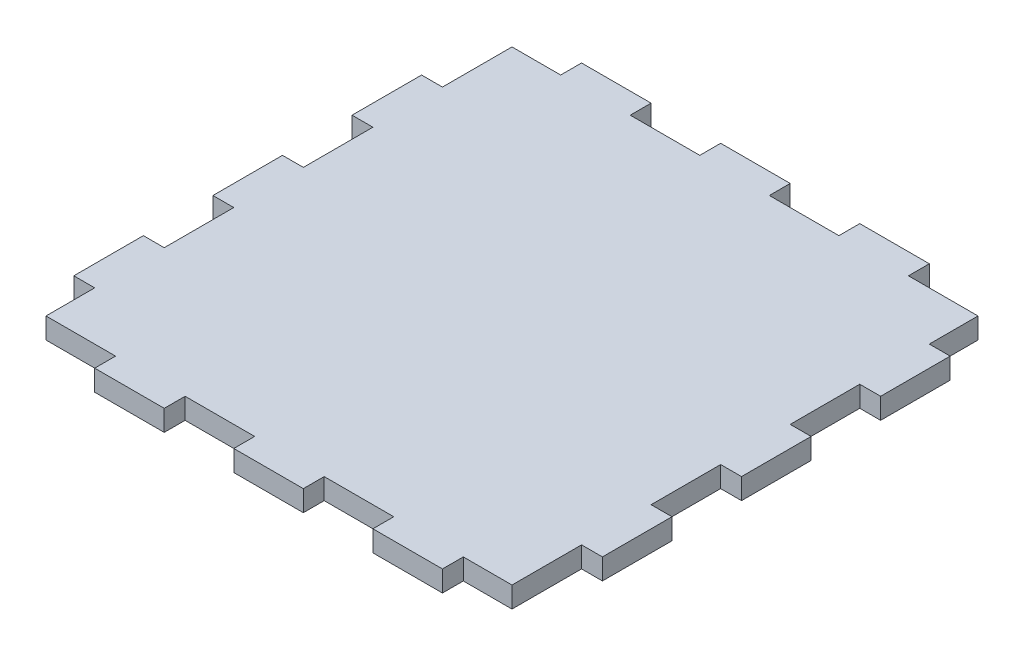
SolidWorks part; units mm, degrees
ref_plane "Front Plane" through (0, 0, 0) normal (0, 0, 1) x (1, 0, 0)
ref_plane "Top Plane" through (0, 0, 0) normal (0, 1, 0) x (1, 0, 0)
ref_plane "Right Plane" through (0, 0, 0) normal (1, 0, 0) x (0, 0, -1)
sketch "Sketch1" plane through (0, 0, 0) normal (0, 1, 0) x (1, 0, 0)
  line L0 (33.5, 16.5) -> (36.5, 16.5)
  line L1 (-33.5, -33.5) -> (33.5, -33.5)
  line L2 (-33.5, -33.5) -> (-33.5, 33.5)
  line L3 (-33.5, 33.5) -> (33.5, 33.5)
  line L4 (33.5, -33.5) -> (33.5, 33.5)
  line L5 (-33.5, -33.5) -> (33.5, 33.5) construction
  line L6 (-33.5, 33.5) -> (33.5, -33.5) construction
  line L7 (-6.5, 33.5) -> (3.5, 33.5)
  line L8 (-6.5, 33.5) -> (-6.5, 36.5)
  line L9 (-6.5, 36.5) -> (3.5, 36.5)
  line L10 (3.5, 33.5) -> (3.5, 36.5)
  line L11 (-6.5, 33.5) -> (3.5, 36.5) construction
  line L12 (-6.5, 36.5) -> (3.5, 33.5) construction
  line L13 (-26.5, 33.5) -> (-16.5, 33.5)
  line L14 (-26.5, 33.5) -> (-26.5, 36.5)
  line L15 (-26.5, 36.5) -> (-16.5, 36.5)
  line L16 (-16.5, 33.5) -> (-16.5, 36.5)
  line L17 (-26.5, 33.5) -> (-16.5, 36.5) construction
  line L18 (-26.5, 36.5) -> (-16.5, 33.5) construction
  line L19 (13.5, 33.5) -> (23.5, 33.5)
  line L20 (13.5, 33.5) -> (13.5, 36.5)
  line L21 (13.5, 36.5) -> (23.5, 36.5)
  line L22 (23.5, 33.5) -> (23.5, 36.5)
  line L23 (13.5, 33.5) -> (23.5, 36.5) construction
  line L24 (13.5, 36.5) -> (23.5, 33.5) construction
  line L25 (36.5, 26.5) -> (36.5, 16.5)
  line L26 (33.5, 26.5) -> (36.5, 26.5)
  line L27 (33.5, 6.5) -> (36.5, 6.5)
  line L28 (36.5, 6.5) -> (36.5, -3.5)
  line L29 (33.5, -3.5) -> (36.5, -3.5)
  line L30 (33.5, -13.5) -> (36.5, -13.5)
  line L31 (36.5, -13.5) -> (36.5, -23.5)
  line L32 (33.5, -23.5) -> (36.5, -23.5)
  line L33 (16.5, -33.5) -> (16.5, -36.5)
  line L34 (26.5, -36.5) -> (16.5, -36.5)
  line L35 (26.5, -33.5) -> (26.5, -36.5)
  line L36 (6.5, -33.5) -> (6.5, -36.5)
  line L37 (6.5, -36.5) -> (-3.5, -36.5)
  line L38 (-3.5, -33.5) -> (-3.5, -36.5)
  line L39 (-13.5, -33.5) -> (-13.5, -36.5)
  line L40 (-13.5, -36.5) -> (-23.5, -36.5)
  line L41 (-23.5, -33.5) -> (-23.5, -36.5)
  line L42 (-33.5, -16.5) -> (-36.5, -16.5)
  line L43 (-36.5, -26.5) -> (-36.5, -16.5)
  line L44 (-33.5, -26.5) -> (-36.5, -26.5)
  line L45 (-33.5, -6.5) -> (-36.5, -6.5)
  line L46 (-36.5, -6.5) -> (-36.5, 3.5)
  line L47 (-33.5, 3.5) -> (-36.5, 3.5)
  line L48 (-33.5, 13.5) -> (-36.5, 13.5)
  line L49 (-36.5, 13.5) -> (-36.5, 23.5)
  line L50 (-33.5, 23.5) -> (-36.5, 23.5)
  point P0 (0, 0)
  point P10 (-1.5, 35)
  point P15 (-21.5, 35)
  point P20 (18.5, 35)
  point P21 (-6.5, 35)
  point P61 (0, 0)
  dimension "D1" = 67
  dimension "D2" = 67
  dimension "D3" = 3
  dimension "D4" = 3
  dimension "D5" = 3
  dimension "D6" = 10
  dimension "D7" = 10
  dimension "D8" = 10
  dimension "D9" = 10
  dimension "D10" = 10
  dimension "D12" = 7
  dimension "D11" = 4
extrude "Boss-Extrude1" add sketch "Sketch1" along normal blind 3 contours L1 L4 L3 L2 | L44 L2 L42 L43 | L2 L47 L46 L45 | L2 L50 L49 L48 | L1 L41 L40 L39 | L1 L38 L37 L36 | L35 L1 L33 L34 | L4 L32 L31 L30 | L4 L29 L28 L27 | L26 L4 L0 L25 | L3 L22 L21 L20 | L3 L10 L9 L8 | L3 L16 L15 L14
sketch "Sketch2" plane through (0, 3, 0) normal (0, 1, 0) x (1, 0, 0)
  line L0 (-33.5, 28.5) -> (33.5, 28.5)
  line L1 (-33.5, 23.5) -> (-33.5, 33.5) construction
  line L2 (33.5, 26.5) -> (33.5, 33.5) construction
sketch "Sketch3" plane through (0, 0, 0) normal (0, -1, 0) x (1, 0, 0)
  line L0 (-135.7232, -654.8177) -> (-802.3899, -654.8177) construction
  line L1 (19.4689, -11.5963) -> (-19.7557, -11.5963) construction
  line L2 (-22.7557, -8.5963) -> (-22.7557, 12.0128) construction
  line L3 (-19.7557, 15.0128) -> (19.4689, 15.0128) construction
  line L4 (22.4689, 12.0128) -> (22.4689, -8.5963) construction
  line L5 (10.2909, -11.5963) -> (10.2909, -13.5661) construction
  line L6 (-13.4873, -5.6818) -> (-20.4372, -5.6818) construction
  line L7 (-13.4873, -5.6818) -> (-13.4873, -1.9803) construction
  line L8 (-13.4873, -1.9803) -> (-20.4372, -1.9803) construction
  line L9 (-20.4372, -5.6818) -> (-20.4372, -1.9803) construction
  line L10 (-13.4873, -5.6818) -> (-20.4372, -1.9803) construction
  line L11 (-13.4873, -1.9803) -> (-20.4372, -5.6818) construction
  line L12 (10.2909, -13.5661) -> (17.5515, -13.5661) construction
  line L13 (17.5515, -13.5661) -> (17.5515, -11.5963) construction
  line L14 (6.6895, -11.5963) -> (6.0489, -15.7334) construction
  line L15 (4.0725, -17.4274) -> (-4.2056, -17.4274) construction
  line L16 (-6.1846, -15.716) -> (-6.7853, -11.5963) construction
  line L17 (2.9535, -15.4274) -> (-3.1747, -15.4274) construction
  line L18 (-3.1747, -13.2705) -> (2.9535, -13.2705) construction
  line L19 (19.4689, -11.9963) -> (-19.7557, -11.9963)
  line L20 (-23.1557, -8.5963) -> (-23.1557, 12.0128)
  line L21 (-19.7557, 15.4128) -> (19.4689, 15.4128)
  line L22 (22.8689, 12.0128) -> (22.8689, -8.5963)
  line L23 (9.8909, -11.5963) -> (9.8909, -13.9661)
  line L24 (9.8909, -13.9661) -> (17.9515, -13.9661)
  line L25 (17.9515, -13.9661) -> (17.9515, -11.5963)
  line L26 (6.2942, -11.5351) -> (5.6537, -15.6722)
  line L27 (4.0725, -17.0274) -> (-4.2056, -17.0274)
  line L28 (-5.7888, -15.6583) -> (-6.3894, -11.5386)
  line L29 (2.9757, -15.8274) -> (-3.2055, -15.8274)
  line L30 (-3.2088, -12.8705) -> (2.9535, -12.8705)
  line L31 (-13.0873, -6.0818) -> (-13.0873, -1.5803)
  line L32 (-13.0873, -1.5803) -> (-20.8372, -1.5803)
  line L33 (-20.8372, -6.0818) -> (-20.8372, -1.5803)
  line L34 (-13.0873, -6.0818) -> (-20.8372, -6.0818)
  line L35 (19.4689, -11.1963) -> (-19.7557, -11.1963)
  line L36 (-22.3557, -8.5963) -> (-22.3557, 12.0128)
  line L37 (-19.7557, 14.6128) -> (19.4689, 14.6128)
  line L38 (22.0689, 12.0128) -> (22.0689, -8.5963)
  line L39 (10.6909, -11.5963) -> (10.6909, -13.1661)
  line L40 (10.6909, -13.1661) -> (17.1515, -13.1661)
  line L41 (17.1515, -13.1661) -> (17.1515, -11.5963)
  line L42 (7.0848, -11.6575) -> (6.4442, -15.7946)
  line L43 (4.0725, -17.8274) -> (-4.2056, -17.8274)
  line L44 (-6.5805, -15.7737) -> (-7.1811, -11.654)
  line L45 (2.9279, -15.0274) -> (-3.1414, -15.0274)
  line L46 (-3.136, -13.6705) -> (2.9543, -13.6705)
  line L47 (-13.8873, -5.2818) -> (-13.8873, -2.3803)
  line L48 (-13.8873, -2.3803) -> (-20.0372, -2.3803)
  line L49 (-20.0372, -5.2818) -> (-20.0372, -2.3803)
  line L50 (-13.8873, -5.2818) -> (-20.0372, -5.2818)
  arc A0 (-19.7557, -11.5963) -> (-22.7557, -8.5963) centre (-19.7557, -8.5963) cw construction
  arc A1 (-22.7557, 12.0128) -> (-19.7557, 15.0128) centre (-19.7557, 12.0128) cw construction
  arc A2 (22.4689, 12.0128) -> (19.4689, 15.0128) centre (19.4689, 12.0128) ccw construction
  arc A3 (22.4689, -8.5963) -> (19.4689, -11.5963) centre (19.4689, -8.5963) cw construction
  circle A4 centre (-0.1532, 1.802) radius 8.133 construction
  circle A5 centre (-0.0323, 1.8026) radius 11.4127 construction
  arc A6 (-6.1846, -15.716) -> (-4.2056, -17.4274) centre (-4.2056, -15.4274) ccw construction
  arc A7 (4.0725, -17.4274) -> (6.0489, -15.7334) centre (4.0725, -15.4274) ccw construction
  arc A8 (-19.7557, -11.9963) -> (-23.1557, -8.5963) centre (-19.7557, -8.5963) cw
  arc A9 (-23.1557, 12.0128) -> (-19.7557, 15.4128) centre (-19.7557, 12.0128) cw
  arc A10 (22.8689, 12.0128) -> (19.4689, 15.4128) centre (19.4689, 12.0128) ccw
  arc A11 (22.8689, -8.5963) -> (19.4689, -11.9963) centre (19.4689, -8.5963) cw
  arc A12 (4.0725, -17.0274) -> (5.6537, -15.6722) centre (4.0725, -15.4274) ccw
  arc A13 (-5.7888, -15.6583) -> (-4.2056, -17.0274) centre (-4.2056, -15.4274) ccw
  circle A14 centre (-0.0323, 1.8026) radius 11.8127
  circle A15 centre (-0.1532, 1.802) radius 8.533
  arc A16 (-19.7557, -11.1963) -> (-22.3557, -8.5963) centre (-19.7557, -8.5963) cw
  arc A17 (-22.3557, 12.0128) -> (-19.7557, 14.6128) centre (-19.7557, 12.0128) cw
  arc A18 (22.0689, 12.0128) -> (19.4689, 14.6128) centre (19.4689, 12.0128) ccw
  arc A19 (22.0689, -8.5963) -> (19.4689, -11.1963) centre (19.4689, -8.5963) cw
  arc A20 (4.0725, -17.8274) -> (6.4442, -15.7946) centre (4.0725, -15.4274) ccw
  arc A21 (-6.5805, -15.7737) -> (-4.2056, -17.8274) centre (-4.2056, -15.4274) ccw
  circle A22 centre (-0.0323, 1.8026) radius 11.0127
  circle A23 centre (-0.1532, 1.802) radius 7.733
  spline S0 degree 3 poles (2.9535, -13.2705) (4.2631, -13.2652) (4.0316, -15.3074) (2.9535, -15.4274) knots 0 0 0 0 1 1 1 1 construction
  spline S1 degree 3 poles (-3.1747, -13.2705) (-4.2119, -13.4488) (-4.4783, -15.2257) (-3.1747, -15.4274) knots 0 0 0 0 1 1 1 1 construction
  spline S2 degree 1 poles (2.9535, -12.8705) (2.9757, -15.8274) knots 0 0 1 1 construction
  spline S3 degree 1 poles (-3.2088, -12.8705) (-3.2055, -15.8274) knots 0 0 1 1 construction
  spline S4 degree 3 poles (2.9535, -12.8705) (3.1569, -12.8699) (3.5851, -12.9561) (4.0181, -13.3353) (4.2328, -13.8259) (4.283, -14.511) (4.0568, -15.1809) (3.536, -15.685) (3.1611, -15.8068) (2.9757, -15.8274) knots 0.000309 0.000309 0.000309 0.000309 0.126123 0.251937 0.377751 0.503565 0.755192 0.881006 1.00682 1.00682 1.00682 1.00682
  spline S5 degree 3 poles (-3.2055, -15.8274) (-3.4024, -15.797) (-3.8048, -15.6744) (-4.36, -15.1614) (-4.5486, -14.2934) (-4.25, -13.4946) (-3.7961, -13.0817) (-3.5141, -12.9465) (-3.3306, -12.8918) (-3.2506, -12.8777) (-3.2088, -12.8705) knots -0.010812 -0.010812 -0.010812 -0.010812 0.116512 0.243835 0.498482 0.75313 0.880453 0.944115 0.975946 1.007777 1.007777 1.007777 1.007777
  spline S6 degree 1 poles (2.9543, -13.6705) (2.9279, -15.0274) knots 0 0 1 1 construction
  spline S7 degree 1 poles (-3.136, -13.6705) (-3.1414, -15.0274) knots 0 0 1 1 construction
  spline S8 degree 3 poles (2.9543, -13.6705) (3.0022, -13.6703) (3.1077, -13.6803) (3.2352, -13.7267) (3.342, -13.8126) (3.4343, -13.9981) (3.475, -14.353) (3.3049, -14.8486) (3.068, -15.0062) (2.9279, -15.0274) knots -0.000204 -0.000204 -0.000204 -0.000204 0.061637 0.123479 0.247161 0.370844 0.494526 0.741891 0.989256 0.989256 0.989256 0.989256
  spline S9 degree 3 poles (-3.1414, -15.0274) (-3.191, -15.0183) (-3.2958, -14.9895) (-3.4383, -14.9166) (-3.559, -14.8003) (-3.6439, -14.6125) (-3.6741, -14.2963) (-3.5208, -13.8708) (-3.2757, -13.7021) (-3.136, -13.6705) knots 0.016139 0.016139 0.016139 0.016139 0.077003 0.137867 0.259595 0.381322 0.50305 0.746506 0.989961 0.989961 0.989961 0.989961
  point P22 (-16.9622, -3.8311)
  dimension "D1" = 3
  dimension "D2" = 2
  dimension "D3" = 0.4
  dimension "D4" = 0.4
extrude "Cut-Extrude1" cut sketch "Sketch3" against normal blind 0.3
